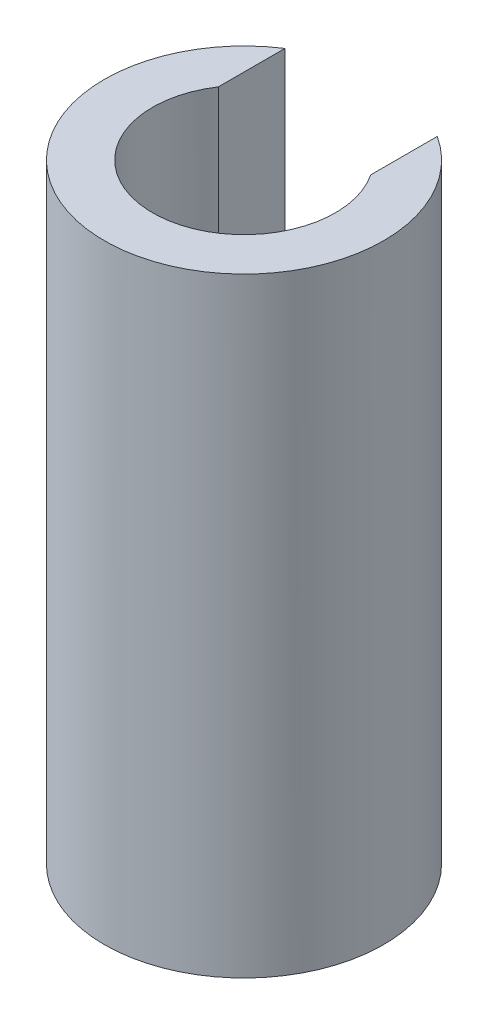
SolidWorks part; units mm, degrees
ref_plane "Front Plane" through (0, 0, 0) normal (0, 0, 1) x (1, 0, 0)
ref_plane "Top Plane" through (0, 0, 0) normal (0, 1, 0) x (1, 0, 0)
ref_plane "Right Plane" through (0, 0, 0) normal (1, 0, 0) x (0, 0, -1)
sketch "Sketch1" plane through (0, 0, 0) normal (0, 1, 0) x (1, 0, 0)
  circle A0 centre (0, 0) radius 2.75
  circle A1 centre (0, 0) radius 1.8
  dimension "D1" = 5.5
  dimension "D2" = 3.6
extrude "Boss-Extrude1" add sketch "Sketch1" along normal blind 12 contours A0
sketch "Sketch3" plane through (0, 0, 0) normal (0, -1, 0) x (1, 0, 0)
  circle A0 centre (0, 0) radius 1.8
  dimension "D1" = 3.6
extrude "Cut-Extrude1" cut sketch "Sketch3" against normal blind 12
sketch "Sketch4" plane through (0, 12, 0) normal (0, 1, 0) x (1, 0, 0)
  line L1 (1.5, 0) -> (-1.5, 0)
  line L2 (1.5, 0) -> (1.5, 2.75)
  line L3 (1.5, 2.75) -> (-1.5, 2.75)
  line L4 (-1.5, 0) -> (-1.5, 2.75)
  circle A0 centre (0, 0) radius 2.75 construction
  point P4 (0, 0)
  dimension "D1" = 3
extrude "Cut-Extrude2" cut sketch "Sketch4" against normal blind 6
